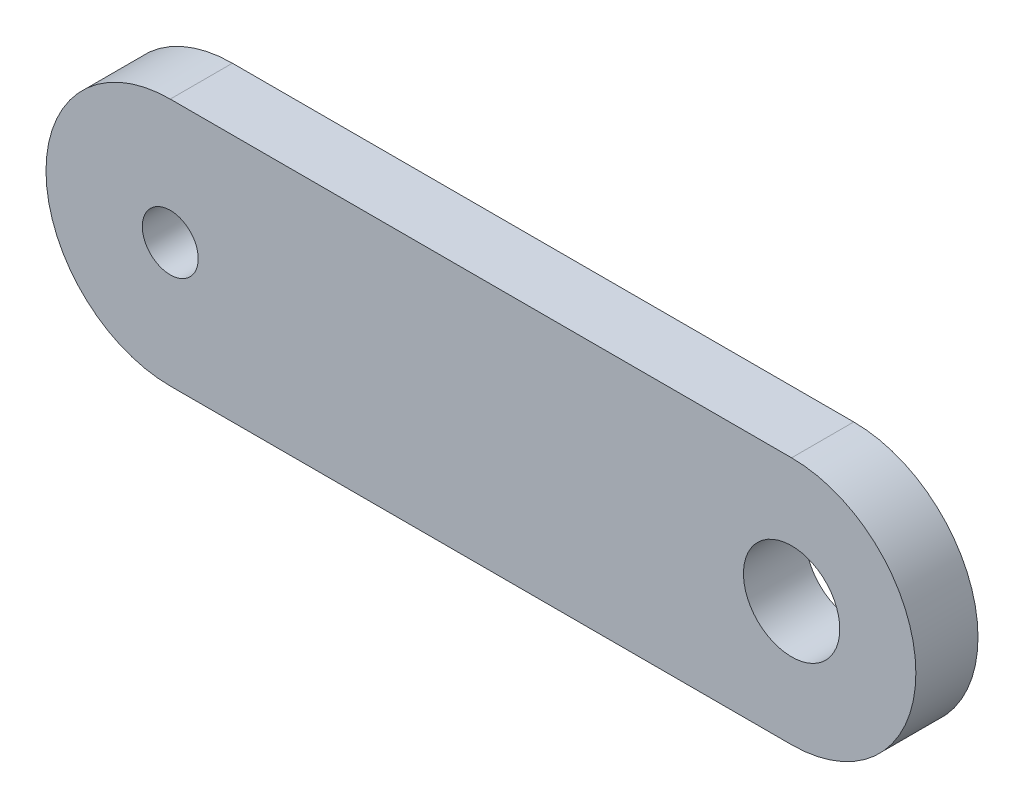
SolidWorks part; units mm, degrees
ref_plane "前视基准面" through (0, 0, 0) normal (0, 0, 1) x (1, 0, 0)
ref_plane "上视基准面" through (0, 0, 0) normal (0, 1, 0) x (1, 0, 0)
ref_plane "右视基准面" through (0, 0, 0) normal (1, 0, 0) x (0, 0, -1)
other "Configuration Table"
sketch "草图1" plane through (0, 0, 0) normal (0, 0, 1) x (1, 0, 0)
  line L0 (10, 0) -> (-10, 0) construction
  line L1 (10, -4) -> (-10, -4)
  line L2 (10, 4) -> (-10, 4)
  arc A0 (10, -4) -> (10, 4) centre (10, 0) ccw
  arc A1 (-10, 4) -> (-10, -4) centre (-10, 0) ccw
  circle A2 centre (10, 0) radius 1.55
  circle A3 centre (-10, 0) radius 0.9
  point P3 (0, 0)
  dimension "D2" = 4
  dimension "D3" = 3.1
  dimension "D4" = 1.8
  dimension "D1" = 20
extrude "凸台-拉伸1" add sketch "草图1" along normal blind 2
